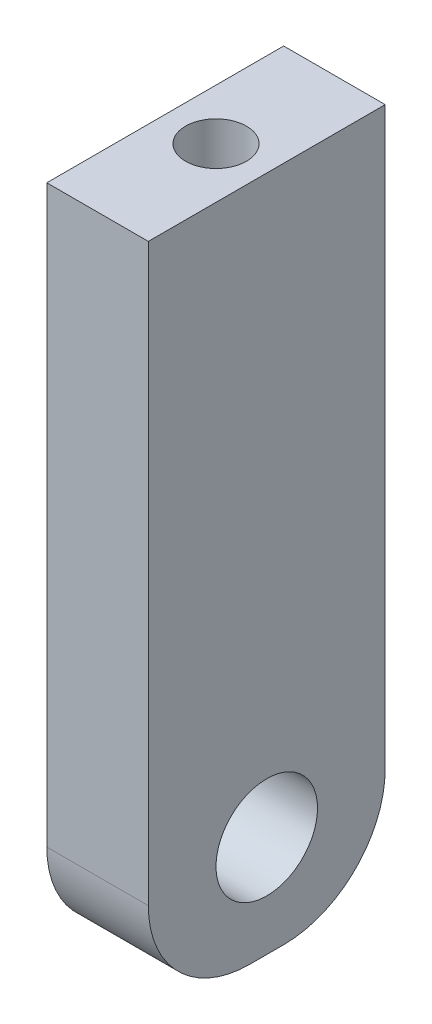
SolidWorks part; units mm, degrees
ref_plane "前视基准面" through (0, 0, 0) normal (0, 0, 1) x (1, 0, 0)
ref_plane "上视基准面" through (0, 0, 0) normal (0, 1, 0) x (1, 0, 0)
ref_plane "右视基准面" through (0, 0, 0) normal (1, 0, 0) x (0, 0, -1)
sketch "草图1" plane through (0, 0, 0) normal (0, 0, 1) x (1, 0, 0)
  line L6 (0, 0.5463) -> (0, -19.4537)
  line L7 (0, -19.4537) -> (3, -19.4537)
  line L8 (3, -19.4537) -> (3, 0.5463)
  line L9 (3, 0.5463) -> (0, 0.5463)
  dimension "D1" = 20
  dimension "D2" = 3
extrude "凸台-拉伸1" add sketch "草图1" along normal blind 7
sketch "草图3" plane through (0, 0.5463, 0) normal (0, 1, 0) x (1, 0, 0)
  line L0 (0, -7) -> (0, 0) construction
  line L1 (3, 0) -> (0, 0) construction
  circle A0 centre (1.5, -3.5) radius 0.9
  point P6 (0, -3.5)
  point P7 (1.5, 0)
  dimension "D1" = 1.8
sketch "草图4" plane through (3, 0, 0) normal (1, 0, 0) x (0, 0, -1)
  line L0 (-7, -19.4537) -> (0, -19.4537) construction
  line L1 (-7, -19.4537) -> (-7, 0.5463) construction
  circle A0 centre (-3.5, -16.4537) radius 1.5
  dimension "D1" = 3
  dimension "D2" = 3
  dimension "D3" = 3.5
extrude "切除-拉伸2" cut sketch "草图4" against normal through all
fillet "圆角1" radius 3 2 edges at (1.5, -19.4537, 7) (1.5, -19.4537, 0)
extrude "切除-拉伸4" cut sketch "草图3" against normal blind 7
